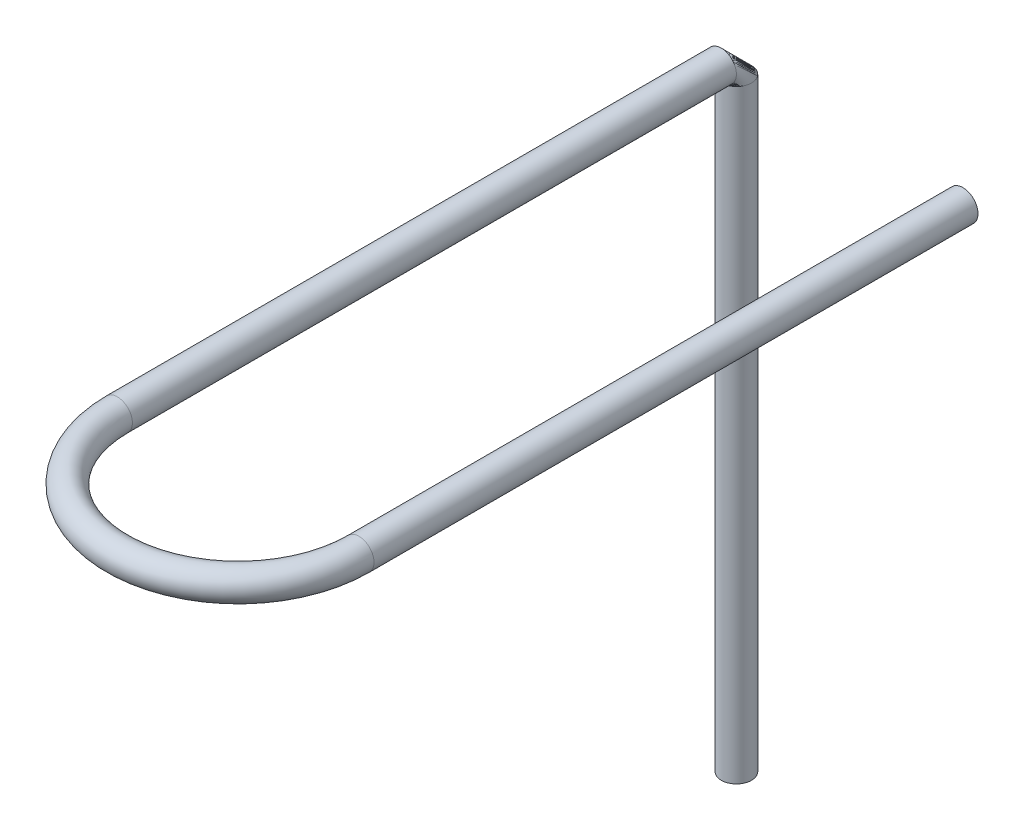
SolidWorks part; units mm, degrees
ref_plane "Plano frontal" through (0, 0, 0) normal (0, 0, 1) x (1, 0, 0)
ref_plane "Plano superior" through (0, 0, 0) normal (0, 1, 0) x (1, 0, 0)
ref_plane "Plano direito" through (0, 0, 0) normal (1, 0, 0) x (0, 0, -1)
sketch "Esboço1" plane through (0, 0, 0) normal (0, 1, 0) x (1, 0, 0)
  line L0 (0, 0) -> (0, -10)
  line L1 (4, -10) -> (4, 0)
  arc A0 (0, -10) -> (4, -10) centre (2, -10) ccw
  dimension "D2" = 2
  dimension "D1" = 10
sketch "Esboço2" plane through (0, 0, 0) normal (1, 0, 0) x (0, 0, -1)
  line L0 (0.25, -0.25) -> (0.25, -10.25)
  arc A0 (0, 0) -> (0.25, -0.25) centre (0, -0.25) cw
  point P3 (0, 0)
  point P6 (0, 0)
  point P7 (0, 0)
  dimension "D1" = 0.25
  dimension "D2" = 10
sweep "Varredura2" add path "Esboço1" circular profile diameter 0.5 parameters "D3"=0.5
sweep "Varredura3" add path "Esboço2" circular profile diameter 0.5 parameters "D3"=0.5
